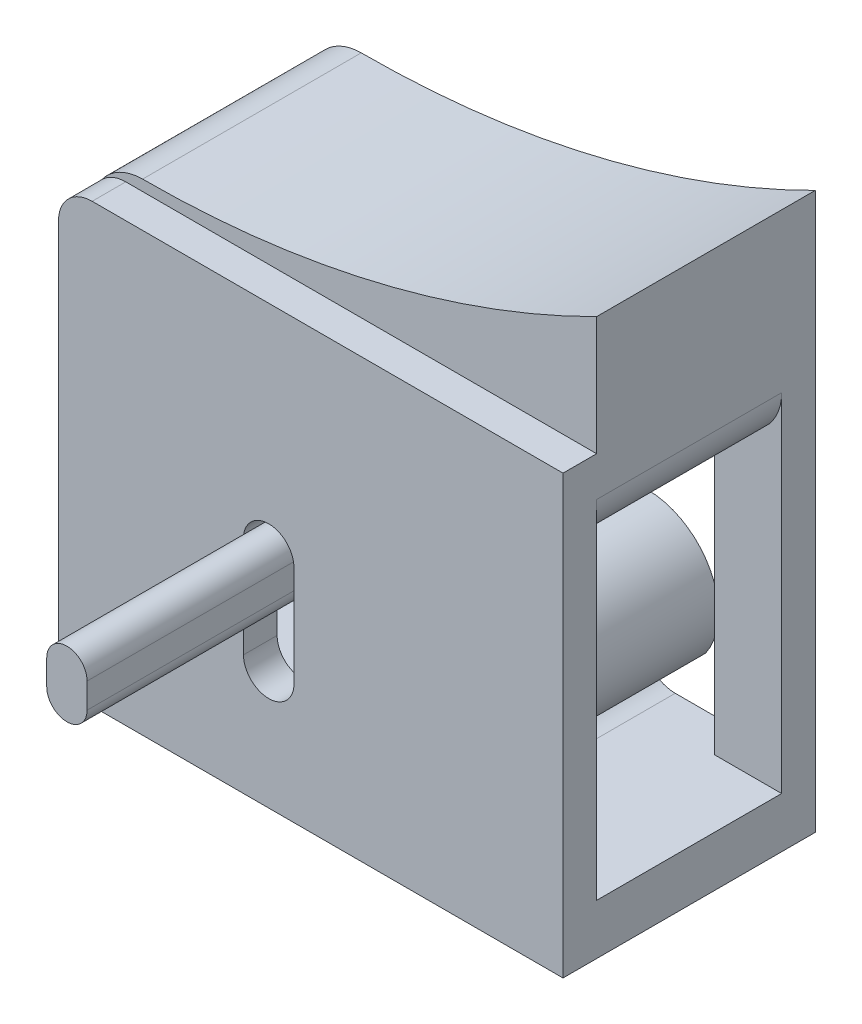
SolidWorks part; units mm, degrees
ref_plane "Front Plane" through (0, 0, 0) normal (0, 0, 1) x (1, 0, 0)
ref_plane "Top Plane" through (0, 0, 0) normal (0, 1, 0) x (1, 0, 0)
ref_plane "Right Plane" through (0, 0, 0) normal (1, 0, 0) x (0, 0, -1)
sketch "Esboço1" plane through (0, 0, 0) normal (0, 0, 1) x (1, 0, 0)
  line L0 (0, -25.1423) -> (0, 0) construction
  line L2 (-9, -1.5) -> (9, -1.5)
  line L3 (-15, -1.5) -> (-15, 1.5) construction
  line L4 (-15, 1.5) -> (15, 1.5) construction
  line L5 (15, -1.5) -> (15, 1.5)
  line L6 (-15, -1.5) -> (15, 1.5) construction
  line L7 (-15, 1.5) -> (15, -1.5) construction
  line L10 (-15, -1.5) -> (-9, -1.5) construction
  line L11 (15, -25.1423) -> (-15, -25.1423)
  line L12 (15, -25.1423) -> (15, -22.1423)
  line L13 (15, -22.1423) -> (4.6745, -22.1423)
  line L14 (-15, -25.1423) -> (-15, -22.1423)
  line L15 (15, -25.1423) -> (-15, -22.1423) construction
  line L16 (15, -22.1423) -> (-15, -25.1423) construction
  line L17 (9, -1.5) -> (15, -1.5) construction
  line L18 (-3.5, -22.1423) -> (-15, -22.1423)
  line L19 (15, 1.5) -> (15, 7.9183)
  line L22 (3.1745, -22.1423) -> (-3.5, -22.1423)
  line L23 (5, -16.7321) -> (0, -16.7321) construction
  line L24 (0, -16.7321) -> (-1, -16.7321) construction
  line L25 (-3.75, -16.7321) -> (-3.75, -11)
  line L26 (-0.75, -15) -> (-0.75, -11)
  line L27 (-3.75, -11) -> (-0.75, -10)
  line L28 (-0.75, -10) -> (-0.75, -11)
  line L29 (3.1745, -22.1423) -> (3.1745, -16.7321)
  line L30 (4.6745, -22.1423) -> (4.6745, -19.7885)
  line L31 (3.1745, -16.7321) -> (4.2423, -16.7321)
  arc A1 (9, -1.5) -> (15, -1.5) centre (12, -1.5) ccw
  arc A2 (-15, -1.5) -> (-9, -1.5) centre (-12, -1.5) ccw
  arc A7 (-15, -1.5) -> (-12, 1.5) centre (-12, -1.5) cw
  arc A8 (-12, 1.5) -> (15, 7.9183) centre (-12, 61.5) ccw
  arc A9 (7.9075, -18.1842) -> (1.75, -16.7321) centre (5, -16.7321) ccw
  arc A10 (8.4751, -19.1787) -> (0.75, -16.7321) centre (5, -16.7321) ccw
  arc A11 (-3.75, -16.7321) -> (1.75, -16.7321) centre (-1, -16.7321) ccw
  arc A12 (-0.75, -15) -> (0.75, -16.7321) centre (-1, -16.7321) ccw
  arc A17 (4.2423, -16.7321) -> (7.9075, -18.1842) centre (6.1994, -17.1439) ccw
  arc A19 (4.6745, -19.7885) -> (8.4751, -19.1787) centre (6.1994, -17.1439) ccw
  point P20 (0, -23.6423)
  point P33 (4.3539, -16.2321)
  point P36 (8.4751, -18.6787)
  dimension "D3" = 6.5
  dimension "D4" = 6
  dimension "D6" = 30
  dimension "D8" = 4
  dimension "D9" = 5
  dimension "D10" = 3
  dimension "D11" = 1
  dimension "D12" = 60
  dimension "D5" = 1
  dimension "D1" = 30
  dimension "D2" = 3
  dimension "D7" = 3
  dimension "D13" = 3
  dimension "D14" = 1
  dimension "D15" = 5
  dimension "D16" = 8.5
  dimension "D17" = 1.5
extrude "Ressalto-extrusão1" add sketch "Esboço1" along normal mid plane 12
sketch "Esboço2" plane through (0, 0, 6) normal (0, 0, 1) x (1, 0, 0)
  line L0 (-15, -25.1423) -> (15, -25.1423) construction
  line L1 (-15, -25.1423) -> (15, -25.1423)
  line L2 (-15, -25.1423) -> (-15, -1.1423)
  line L3 (-13, 0.8577) -> (15, 0.8577)
  line L4 (15, -25.1423) -> (15, 0.8577)
  line L5 (-15, -25.1423) -> (15, 0.8577) construction
  line L6 (-15, 0.8577) -> (15, -25.1423) construction
  line L7 (0, 0) -> (-2.5, 0) construction
  line L8 (-2.5, 0) -> (-2.5, -12) construction
  line L9 (-2.5, -12) -> (-2.5, -18) construction
  line L10 (-1, -12) -> (-1, -18)
  line L13 (-15, -22.1423) -> (-15, -25.1423) construction
  line L14 (-4, -12) -> (-4, -18)
  arc A0 (-1, -12) -> (-4, -12) centre (-2.5, -12) ccw
  arc A3 (-15, -1.1423) -> (-13, 0.8577) centre (-13, -1.1423) cw
  arc A4 (-4, -18) -> (-1, -18) centre (-2.5, -18) ccw
  point P0 (0, -12.1423)
  point P11 (-2.5, -15)
  point P19 (-2.7815, -11.9024)
  dimension "D1" = 1.5
  dimension "D6" = 2
  dimension "D2" = 6
  dimension "D3" = 26
  dimension "D4" = 30
  dimension "D5" = 2.5
  dimension "D7" = 12
extrude "Ressalto-extrusão2" add sketch "Esboço2" along normal blind 2 from offset 1
sketch "Esboço3" plane through (0, 0, 6) normal (0, 0, 1) x (1, 0, 0)
  line L0 (15, -22.1423) -> (15, -25.1423)
  line L1 (15, -25.1423) -> (-15, -25.1423)
  line L2 (-15, -25.1423) -> (-15, -22.1423)
  line L3 (-15, -22.1423) -> (15, -22.1423)
  line L4 (15, -1.5) -> (15, 7.9183)
  line L7 (-9, -1.5) -> (9, -1.5)
  line L8 (15, -1.5) -> (15, 7.9183)
  line L11 (-9, -1.5) -> (9, -1.5)
  arc A2 (-12, 1.5) -> (-9, -1.5) centre (-12, -1.5) ccw
  arc A3 (9, -1.5) -> (15, -1.5) centre (12, -1.5) ccw
  arc A4 (-12, 1.5) -> (-9, -1.5) centre (-12, -1.5) ccw
  arc A5 (9, -1.5) -> (15, -1.5) centre (12, -1.5) ccw
  arc A7 (-12, 1.5) -> (15, 7.9183) centre (-12, 61.5) ccw
  arc A8 (-12, 1.5) -> (15, 7.9183) centre (-12, 61.5) ccw
  dimension "D1" = 0
extrude "Ressalto-extrusão4" add sketch "Esboço3" along normal blind 1
sketch "Esboço4" plane through (0, 0, 6) normal (0, 0, 1) x (1, 0, 0)
  line L0 (-2.5, -12) -> (-2.5, -13.5) construction
  line L1 (-2.5, -12) -> (-2.5, -13.5) construction
  line L2 (-1.3, -12) -> (-1.3, -13.5)
  line L3 (-3.7, -12) -> (-3.7, -13.5)
  arc A1 (-1, -12) -> (-4, -12) centre (-2.5, -12) ccw construction
  arc A2 (-1, -12) -> (-4, -12) centre (-2.5, -12) ccw construction
  arc A4 (-1.3, -12) -> (-3.7, -12) centre (-2.5, -12) ccw
  arc A5 (-3.7, -13.5) -> (-1.3, -13.5) centre (-2.5, -13.5) ccw
  point P3 (-2.5, -12.75)
  point P9 (-3.7, -13.5)
  dimension "D1" = 1.5
  dimension "D2" = 1.2
sketch "Esboço5" plane through (0, 0, -6) normal (0, 0, -1) x (-1, 0, 0)
  line L0 (-15, -25.1423) -> (-15, 0.8577) construction
  line L1 (-15, -25.1423) -> (-15, 0.8577)
  line L2 (-15, 0.8577) -> (-11, 0.8577)
  line L3 (-11, 0.8577) -> (-11, -25.1423)
  line L4 (15, -25.1423) -> (-15, -25.1423) construction
  line L5 (-11, -25.1423) -> (-15, -25.1423)
  line L6 (6.25, -25.1423) -> (6.25, 0.8577)
  line L7 (6.25, 0.8577) -> (12.25, 0.8577)
  line L8 (15, -1.8923) -> (15, -25.1423)
  line L9 (15, -25.1423) -> (6.25, -25.1423)
  line L10 (15, -22.1423) -> (15, -25.1423) construction
  arc A1 (12.25, 0.8577) -> (15, -1.8923) centre (12.25, -1.8923) cw
  point P8 (0, 0)
  point P13 (0, 0)
  dimension "D2" = 2.75
  dimension "D1" = 4
  dimension "D3" = 6
extrude "Ressalto-extrusão6" add sketch "Esboço5" against normal blind 2
extrude "Ressalto-extrusão7" add sketch "Esboço4" along normal blind 15
fillet "Filete7" radius 2 2 edges at (4.6745, -22.1423, 0) (3.1745, -22.1423, 0)
fillet "Filete8" radius 0.5 2 edges at (4.2423, -16.7321, 0) (3.1745, -16.7321, 0)
fillet "Filete9" radius 2 1 edges at (-0.75, -15, 0)
